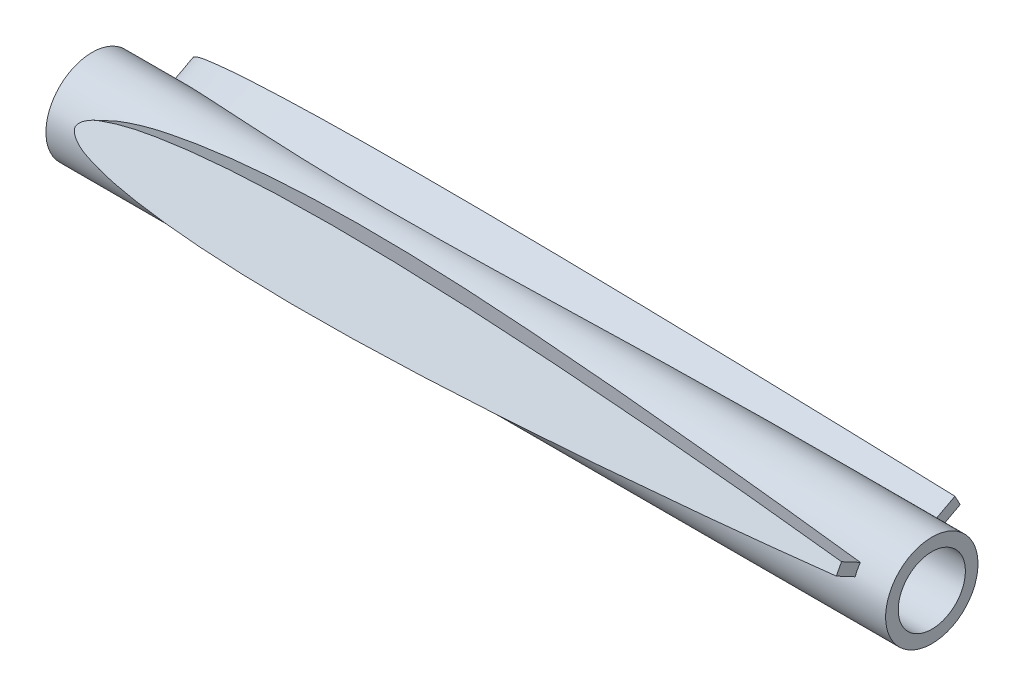
SolidWorks part; units mm, degrees
ref_plane "Front Plane" through (0, 0, 0) normal (0, 0, 1) x (1, 0, 0)
ref_plane "Top Plane" through (0, 0, 0) normal (0, 1, 0) x (1, 0, 0)
ref_plane "Right Plane" through (0, 0, 0) normal (1, 0, 0) x (0, 0, -1)
sketch "Эскиз4" plane through (0, 0, 0) normal (0, 0, 1) x (1, 0, 0)
  line L0 (0, 0) -> (-190.9268, 0) construction
ref_plane "Плоскость2" through (0, 0, 0) normal (0, -0.4695, 0.8829) x (-1, 0, 0)
curve "Кривая2"
  spline degree 3 poles (195, 0.1446, 0.0769) (191.7503, 0.4076, 0.2167) (185.2523, 0.9335, 0.4963) (172.2543, 1.9127, 1.0169) (156.0064, 3.0366, 1.6144) (136.5058, 4.2319, 2.2499) (117.0061, 5.2717, 2.8027) (97.5059, 6.116, 3.2517) (78.0051, 6.72, 3.5728) (61.7506, 6.9306, 3.6848) (48.7484, 6.8474, 3.6405) (38.9957, 6.6202, 3.5197) (29.2371, 6.1855, 3.2886) (21.113, 5.5745, 2.9638) (14.6037, 4.8451, 2.576) (9.7375, 4.1386, 2.2003) (5.5568, 3.2162, 1.7099) (2.2726, 2.2745, 1.2092) (-1.296, 0, 0) (2.2726, -2.2745, -1.2092) (5.5568, -3.2162, -1.7099) (9.7375, -4.1386, -2.2003) (14.6037, -4.8451, -2.576) (21.113, -5.5745, -2.9638) (29.2371, -6.1855, -3.2886) (38.9957, -6.6202, -3.5197) (48.7484, -6.8474, -3.6405) (61.7506, -6.9306, -3.6848) (78.0051, -6.72, -3.5728) (97.5059, -6.116, -3.2517) (117.0061, -5.2717, -2.8027) (136.5058, -4.2319, -2.2499) (156.0064, -3.0366, -1.6144) (172.2543, -1.9127, -1.0169) (185.2523, -0.9335, -0.4963) (191.7503, -0.4076, -0.2167) (195, -0.1446, -0.0769) knots 0 0 0 0 0.024876 0.049742 0.099443 0.149112 0.198751 0.248359 0.297937 0.347491 0.372267 0.397051 0.421859 0.446731 0.45922 0.471791 0.48456 0.491195 0.5 0.508805 0.51544 0.528209 0.54078 0.553269 0.578141 0.602949 0.627733 0.652509 0.702063 0.751641 0.801249 0.850888 0.900557 0.950258 0.975124 1 1 1 1
sketch "Эскиз5" plane through (0, 0, 0) normal (0, -0.4695, 0.8829) x (-1, 0, 0)
  line L0 (-182, -1.3314) -> (-182, 1.3314)
  line L1 (0, 0) -> (0, -20.2138) construction
  spline S0 degree 3 poles (-1090.5141, -2820.9233) (-613.9595, 82.5122) (-398.4311, 17.1316) (-172.2543, -2.1663) (-156.0064, -3.439) (-136.5058, -4.7928) (-117.0061, -5.9704) (-97.5059, -6.9267) (-78.0051, -7.6107) (-61.7506, -7.8493) (-48.7484, -7.755) (-38.9957, -7.4977) (-29.2371, -7.0053) (-21.113, -6.3134) (-14.6037, -5.4873) (-9.7375, -4.6872) (-5.5568, -3.6425) (-2.2726, -2.5759) (1.296, 0) (-2.2726, 2.5759) (-5.5568, 3.6425) (-9.7375, 4.6872) (-14.6037, 5.4873) (-21.113, 6.3134) (-29.2371, 7.0053) (-38.9957, 7.4977) (-48.7484, 7.755) (-61.7506, 7.8493) (-78.0051, 7.6107) (-97.5059, 6.9267) (-117.0061, 5.9704) (-136.5058, 4.7928) (-156.0064, 3.439) (-172.2543, 2.1663) (-398.4306, -17.1316) (-613.9586, -82.5119) (-1090.511, 2820.9046) knots -1.630961 -1.630961 -1.630961 -1.630961 0.024876 0.049742 0.099443 0.149112 0.198751 0.248359 0.297937 0.347491 0.372267 0.397051 0.421859 0.446731 0.45922 0.471791 0.48456 0.491195 0.5 0.508805 0.51544 0.528209 0.54078 0.553269 0.578141 0.602949 0.627733 0.652509 0.702063 0.751641 0.801249 0.850888 0.900557 0.950258 0.975124 2.630958 2.630958 2.630958 2.630958 only from (-195, -0.1638) to (-195, 0.1638) construction
  spline S1 degree 3 poles (-182, -1.3314) (-179.8337, -1.5187) (-171.1702, -2.2512) (-156.0064, -3.439) (-136.5058, -4.7928) (-117.0061, -5.9704) (-97.5059, -6.9267) (-78.0051, -7.6107) (-61.7506, -7.8493) (-48.7484, -7.755) (-38.9957, -7.4977) (-29.2371, -7.0053) (-21.113, -6.3134) (-14.6037, -5.4873) (-9.7375, -4.6872) (-5.5568, -3.6425) (-2.2726, -2.5759) (0, -0.9355) (0, 0) knots 0.033166 0.033166 0.033166 0.033166 0.049742 0.099443 0.149112 0.198751 0.248359 0.297937 0.347491 0.372267 0.397051 0.421859 0.446731 0.45922 0.471791 0.48456 0.491195 0.5 0.5 0.5 0.5
  spline S2 degree 3 poles (0, 0) (0, 0.9355) (-2.2726, 2.5759) (-5.5568, 3.6425) (-9.7375, 4.6872) (-14.6037, 5.4873) (-21.113, 6.3134) (-29.2371, 7.0053) (-38.9957, 7.4977) (-48.7484, 7.755) (-61.7506, 7.8493) (-78.0051, 7.6107) (-97.5059, 6.9267) (-117.0061, 5.9704) (-136.5058, 4.7928) (-156.0064, 3.439) (-171.1702, 2.2512) (-179.8337, 1.5187) (-182, 1.3314) knots 0.5 0.5 0.5 0.5 0.508805 0.51544 0.528209 0.54078 0.553269 0.578141 0.602949 0.627733 0.652509 0.702063 0.751641 0.801249 0.850888 0.900557 0.950258 0.966834 0.966834 0.966834 0.966834
  dimension "D1" = 182
sketch "Эскиз6" plane through (0, 0, 0) normal (1, 0, 0) x (0, 0, -1)
  line L0 (0, 0) -> (17.6146, 0) construction
  line L1 (0, 0) -> (-14.1272, -7.5115) construction
  line L2 (-14.1272, 0.4885) -> (-14.1272, -15.5115) construction
  circle A0 centre (-14.1272, -7.5115) radius 8
  circle A1 centre (-14.1272, -7.5115) radius 11
  dimension "D2" = 16
  dimension "D3" = 8
  dimension "D1" = 28
  dimension "D4" = 3
extrude "Бобышка-Вытянуть1" add sketch "Эскиз6" along normal blind 190 and the other way blind 10
extrude "Бобышка-Вытянуть2" add sketch "Эскиз5" along normal up to body separate body
ref_plane "Плоскость3" through (0, 0, 14.1272) normal (0, 0, 1) x (1, 0, 0)
mirror "Зеркальное отражение1" about plane through (0, 0, 14.1272) normal (0, 0, 1) of "Бобышка-Вытянуть2"
equation "\"D6@Fus\"=\"DMotor\"+1.2"
equation "\"D1@Fus\"=\"FusLenght\""
equation "\"D2@Fus\"=\"MotorArm\""
equation "\"D4@Fus\"=\"DFus\""
equation "\"D5@Fus\" = \"FusCentralPartLenght\""
equation "\"D8@Fus\"=\"FusTubeHeight\""
equation "\"D9@Fus\"=\"DFusTube\"+1.2"
equation "\"D11@Fus\"=\"FusNoseLenght\""
equation "\"D3@Fus\"=\"WingOffset\""
equation "\"D19@Бобышка-Вытянуть1\" = \"CenterSectionLenght\" / 2"
equation "\"D4@FusCopy\" = \"FusTubeHeight\""
equation "\"D1@CentralPartCrossSection1\"=\"DFus\"*\"EllipseRatio\""
equation "\"D1@CentralPartCrossSection2\"=\"DFus\"*\"EllipseRatio\""
equation "\"D2@Frame\" = \"DFusTube\" + 1.2"
equation "\"DTailTube\"= 16мм'Диаметр трубки хвостового оперения"
equation "\"FusLenght\"= 700мм"
equation "\"DMotor\"= 35.2мм"
equation "\"MotorArm\"= 225мм"
equation "\"DFus\"= 130мм"
equation "\"DFusTube\"= 16мм'Диаметр трубки внутри фюзеляжа"
equation "\"FusTubeHeight\"= 30мм"
equation "\"FusCentralPartLenght\"= 350мм"
equation "\"FusNoseLenght\"= 170мм"
equation "\"WingOffset\"= 1мм'Расстояние от внутренней поверхности фюзеляжа до профиля крыла по вертикали"
equation "\"EllipseRatio\"= 1.1'Центральная часть фюзеляжа - эллипс. Этот параметр - отношение длин осей эллипса"
equation "\"FrameOffset\"= 0.6мм"
equation "\"DThreadedInsert\"= 3.6мм'Внешний диамер резьбовых втулок"
equation "\"CenterSectionLenght\"= 140мм'Длина центроплана"
equation "\"b\"= 1680мм'Размах"
equation "\"cwr\"= 236мм'Корневая хорда крыла"
equation "\"TR\"= 0.75'Сужение крыла"
equation "\"cwt\"= \"TR\" * \"cwr\"'Концевая хорда крыла"
equation "\"D3@Airfoil\"=\"cwr\""
equation "\"DWingMainSpar\"= 16мм'Диаметр главного лонжерона крыла"
equation "\"DWingSecondSpar\"= 8мм'Диаметр второго лонжерона крыла"
equation "\"WingSparsDistance\"= 80мм'Расстояния между отверстиями по лонжерон крыла"
equation "\"D7@Airfoil\"=\"DWingMainSpar\""
equation "\"D9@Airfoil\"=\"DWingSecondSpar\""
equation "\"D8@Airfoil\"=\"WingSparsDistance\"*2"
equation "\"c\"= 210мм'САХ крыла"
equation "\"D2@Эскиз6\"=\"DTailTube\""
